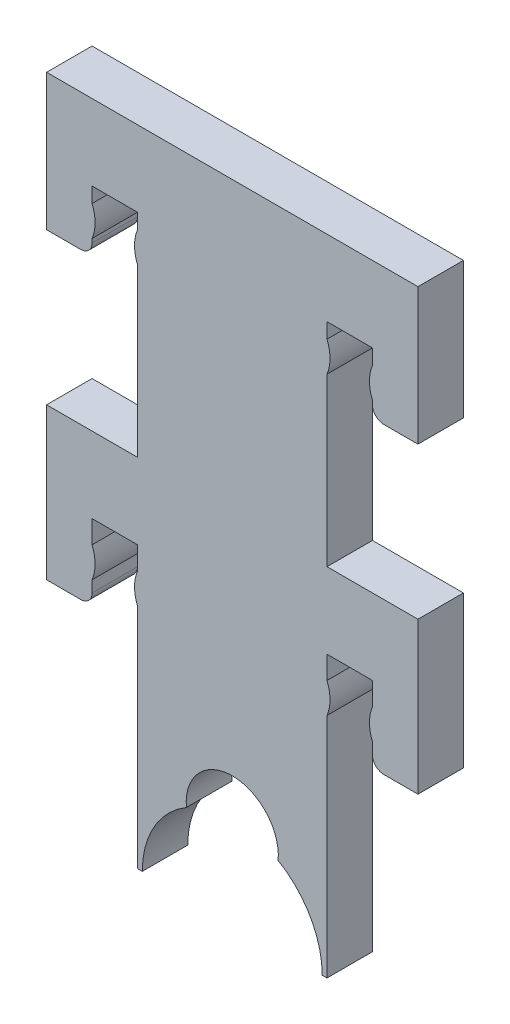
SolidWorks part; units mm, degrees
ref_plane "Front Plane" through (0, 0, 0) normal (0, 0, 1) x (1, 0, 0)
ref_plane "Top Plane" through (0, 0, 0) normal (0, 1, 0) x (1, 0, 0)
ref_plane "Right Plane" through (0, 0, 0) normal (1, 0, 0) x (0, 0, -1)
sketch "Sketch1" plane through (0, 0, 0) normal (0, 0, 1) x (1, 0, 0)
  line L0 (-11.6599, 24.1471) -> (12.8401, 24.1471)
  line L1 (12.8401, 24.1471) -> (12.8401, 15.1471)
  line L2 (12.8401, 15.1471) -> (9.8401, 15.1471)
  line L3 (9.8401, 15.1471) -> (9.8401, 16.1471)
  line L4 (9.8401, 19.1471) -> (6.8401, 19.1471)
  line L5 (6.8401, 19.1471) -> (6.8401, 18.1471)
  line L6 (6.8401, 5.1471) -> (12.8401, 5.1471)
  line L7 (12.8401, 5.1471) -> (12.8401, -4.8529)
  line L8 (12.8401, -4.8529) -> (9.8401, -4.8529)
  line L9 (9.8401, -4.8529) -> (9.8401, -3.3529)
  line L10 (9.8401, 0.1471) -> (6.8401, 0.1471)
  line L11 (6.8401, 0.1471) -> (6.8401, -1.3529)
  line L12 (0.5901, 29.6322) -> (0.5901, 15.1471) construction
  line L13 (-5.6599, 0.1471) -> (-5.6599, -1.3529)
  line L14 (-8.6599, 0.1471) -> (-5.6599, 0.1471)
  line L15 (-8.6599, -4.8529) -> (-8.6599, -3.3529)
  line L16 (-11.6599, -4.8529) -> (-8.6599, -4.8529)
  line L17 (-11.6599, 5.1471) -> (-11.6599, -4.8529)
  line L18 (-5.6599, 5.1471) -> (-11.6599, 5.1471)
  line L19 (-5.6599, 19.1471) -> (-5.6599, 18.1471)
  line L20 (-8.6599, 19.1471) -> (-5.6599, 19.1471)
  line L21 (-8.6599, 15.1471) -> (-8.6599, 16.1471)
  line L22 (-11.6599, 15.1471) -> (-8.6599, 15.1471)
  line L23 (-11.6599, 24.1471) -> (-11.6599, 15.1471)
  line L24 (6.8401, -18.3529) -> (6.5251, -18.3529)
  line L25 (-5.6599, -18.3529) -> (-5.3449, -18.3529)
  line L26 (6.8401, 16.1471) -> (6.8401, 5.1471)
  line L27 (9.8401, 18.1471) -> (9.8401, 19.1471)
  line L28 (9.8401, -1.3529) -> (9.8401, 0.1471)
  line L29 (8.3401, 19.1471) -> (8.3401, 21.1075) construction
  line L30 (8.3401, 0.1471) -> (8.3401, 1.012) construction
  line L31 (6.8401, -3.3529) -> (6.8401, -18.3529)
  line L32 (-8.6599, -1.3529) -> (-8.6599, 0.1471)
  line L33 (-5.6599, -3.3529) -> (-5.6599, -18.3529)
  line L34 (-8.6599, 18.1471) -> (-8.6599, 19.1471)
  line L35 (-5.6599, 16.1471) -> (-5.6599, 5.1471)
  circle A0 centre (0.5901, -12.9629) radius 3.04
  circle A1 centre (0.5901, -18.3529) radius 5.935
  arc A2 (9.8401, 16.1471) -> (9.8401, 18.1471) centre (12.2401, 17.1471) cw
  arc A3 (6.8401, 16.1471) -> (6.8401, 18.1471) centre (4.4401, 17.1471) ccw
  arc A4 (9.8401, -3.3529) -> (9.8401, -1.3529) centre (12.2401, -2.3529) cw
  arc A5 (6.8401, -3.3529) -> (6.8401, -1.3529) centre (4.4401, -2.3529) ccw
  arc A6 (-8.6599, -3.3529) -> (-8.6599, -1.3529) centre (-11.0599, -2.3529) ccw
  arc A7 (-5.6599, -3.3529) -> (-5.6599, -1.3529) centre (-3.2599, -2.3529) cw
  arc A8 (-5.6599, 16.1471) -> (-5.6599, 18.1471) centre (-3.2599, 17.1471) cw
  arc A9 (-8.6599, 16.1471) -> (-8.6599, 18.1471) centre (-11.0599, 17.1471) ccw
  point P27 (0.5901, 24.1471)
  dimension "D11" = 42.5
  dimension "D12" = 37.11
  dimension "D13" = 6.08
  dimension "D14" = 11.87
  dimension "D1" = 9
  dimension "D2" = 3
  dimension "D3" = 3
  dimension "D4" = 12.25
  dimension "D5" = 14
  dimension "D6" = 6
  dimension "D7" = 10
  dimension "D8" = 3
  dimension "D9" = 3
  dimension "D10" = 18.5
  dimension "D15" = 4
  dimension "D16" = 5
  dimension "D17" = 5
extrude "Boss-Extrude1" add sketch "Sketch1" along normal blind 3
fillet "Fillet1" radius 0.75 4 edges at (-8.6599, 15.1471, 1.5) (-8.6599, -4.8529, 1.5) (9.8401, -4.8529, 1.5) (9.8401, 15.1471, 1.5)
